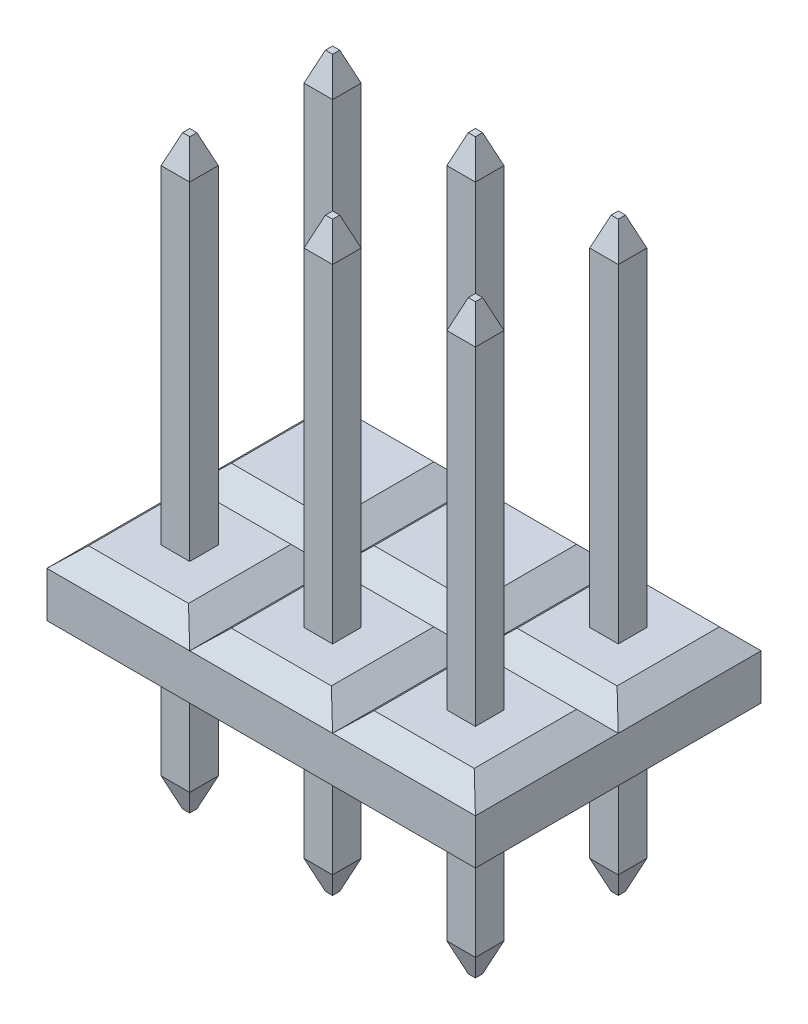
SolidWorks part; units mm, degrees
ref_plane "Front Plane" through (0, 0, 0) normal (0, 0, 1) x (1, 0, 0)
ref_plane "Top Plane" through (0, 0, 0) normal (0, 1, 0) x (1, 0, 0)
ref_plane "Right Plane" through (0, 0, 0) normal (1, 0, 0) x (0, 0, -1)
sketch "Sketch1" plane through (0, 0, 0) normal (0, 1, 0) x (1, 0, 0)
  line L1 (0, 0) -> (2.54, 0)
  line L2 (0, 0) -> (0, 2.54)
  line L3 (0, 2.54) -> (2.54, 2.54)
  line L4 (2.54, 0) -> (2.54, 2.54)
  dimension "D1" = 2.54
  dimension "D2" = 2.54
extrude "Boss-Extrude1" add sketch "Sketch1" along normal blind 1.524
sketch "Sketch2" plane through (0, 1.524, 0) normal (0, 1, 0) x (1, 0, 0)
  line L0 (0, 2.54) -> (0, 0) construction
  line L1 (0, 0) -> (2.54, 0) construction
  line L2 (1.27, 0) -> (1.27, 2.0363) construction
  line L3 (1.524, 1.524) -> (1.016, 1.524)
  line L4 (1.524, 1.524) -> (1.524, 1.016)
  line L5 (1.524, 1.016) -> (1.016, 1.016)
  line L6 (1.016, 1.524) -> (1.016, 1.016)
  line L7 (1.524, 1.524) -> (1.016, 1.016) construction
  line L8 (1.524, 1.016) -> (1.016, 1.524) construction
  line L9 (0, 1.27) -> (2.1183, 1.27) construction
  point P0 (0, 1.27)
  point P1 (1.27, 0)
  point P4 (1.27, 1.27)
  point P7 (1.27, 1.27)
  dimension "D1" = 0.508
  dimension "D2" = 0.508
  dimension "D3" = 0
  dimension "D4" = 0
extrude "Boss-Extrude2" add sketch "Sketch2" along normal blind 6.35
sketch "Sketch3" plane through (0, 0, 0) normal (0, -1, 0) x (1, 0, 0)
  line L4 (1.016, -1.016) -> (1.016, -1.524)
  line L5 (1.524, -1.016) -> (1.016, -1.016)
  line L6 (1.524, -1.524) -> (1.524, -1.016)
  line L7 (1.016, -1.524) -> (1.524, -1.524)
  line L8 (1.016, -1.016) -> (1.016, -1.524)
  line L9 (1.524, -1.016) -> (1.016, -1.016)
  line L10 (1.524, -1.524) -> (1.524, -1.016)
  line L11 (1.016, -1.524) -> (1.524, -1.524)
  dimension "D1" = 0
extrude "Boss-Extrude3" add sketch "Sketch3" along normal blind 2.54
chamfer "Chamfer1" distance 0.508 distance2 0.1905 4 edges at (1.524, 7.874, -1.27) (1.27, 7.874, -1.524) (1.016, 7.874, -1.27) (1.27, 7.874, -1.016)
chamfer "Chamfer2" distance 0.508 distance2 0.1905 4 edges at (1.524, -2.54, -1.27) (1.27, -2.54, -1.524) (1.016, -2.54, -1.27) (1.27, -2.54, -1.016)
sketch "Sketch4" plane through (0, 0, -2.54) normal (0, 0, -1) x (-1, 0, 0)
  line L0 (-2.54, 1.1645) -> (-2.159, 1.524)
  line L1 (-2.54, 1.524) -> (-2.54, 0) construction
  line L2 (-2.54, 1.524) -> (0, 1.524) construction
  line L3 (-2.159, 1.524) -> (-2.54, 1.524)
  line L4 (-2.54, 1.524) -> (-2.54, 1.1645)
  line L5 (-1.27, 1.524) -> (-1.27, 0) construction
  line L6 (-2.54, 0) -> (0, 0) construction
  line L7 (-2.54, 0.762) -> (0, 0.762) construction
  line L8 (0, 1.524) -> (0, 0) construction
  line L9 (0, 1.524) -> (0, 1.1645)
  line L10 (-0.381, 1.524) -> (0, 1.524)
  line L11 (0, 1.1645) -> (-0.381, 1.524)
  line L12 (0, 0.3595) -> (-0.381, 0)
  line L13 (-0.381, 0) -> (0, 0)
  line L14 (0, 0) -> (0, 0.3595)
  line L15 (-2.54, 0) -> (-2.54, 0.3595)
  line L16 (-2.159, 0) -> (-2.54, 0)
  line L17 (-2.54, 0.3595) -> (-2.159, 0)
  dimension "D1" = 0.381
extrude "Cut-Extrude1" cut sketch "Sketch4" against normal blind 2.54
sketch "Sketch5" plane through (0, 0, 0) normal (-1, 0, 0) x (0, 0, 1)
  line L0 (-2.54, 1.1645) -> (-2.159, 1.5455)
  line L1 (-2.159, 1.5455) -> (-2.54, 1.5455)
  line L2 (-2.54, 1.5455) -> (-2.54, 1.1645)
  line L3 (0, 1.1645) -> (-2.54, 1.1645) construction
  line L4 (-2.54, 0.762) -> (0, 0.762) construction
  line L5 (-2.54, 1.1645) -> (-2.54, 0.3595) construction
  line L6 (0, 1.1645) -> (0, 0.3595) construction
  line L7 (-1.27, 0.762) -> (-1.27, 1.5455) construction
  line L8 (0, 1.5455) -> (0, 1.1645)
  line L9 (-0.381, 1.5455) -> (0, 1.5455)
  line L10 (0, 1.1645) -> (-0.381, 1.5455)
  line L11 (-2.54, -0.0215) -> (-2.54, 0.3595)
  line L12 (-2.159, -0.0215) -> (-2.54, -0.0215)
  line L13 (-2.54, 0.3595) -> (-2.159, -0.0215)
  line L14 (0, 0.3595) -> (-0.381, -0.0215)
  line L15 (-0.381, -0.0215) -> (0, -0.0215)
  line L16 (0, -0.0215) -> (0, 0.3595)
  dimension "D1" = 0.381
  dimension "D2" = 0.381
  dimension "D3" = 0.381
extrude "Cut-Extrude2" cut sketch "Sketch5" against normal blind 2.54
pattern_linear "LPattern5" count 2 spacing 2.54 along (0, 0, 1) count 3 spacing 2.54 along (1, 0, 0) of "Boss-Extrude1", "Boss-Extrude2", "Chamfer1", "Chamfer2", "Boss-Extrude3", "Cut-Extrude1", "Cut-Extrude2"
